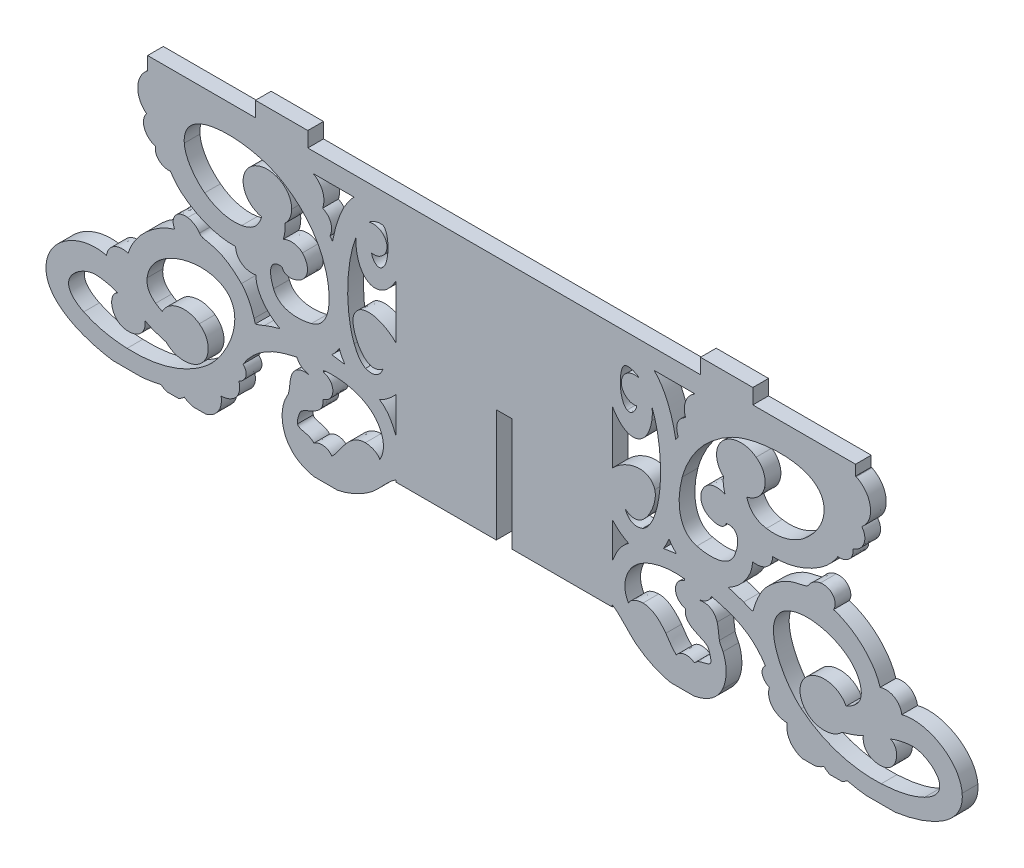
SolidWorks part; units mm, degrees
ref_plane "Plano frontal" through (0, 0, 0) normal (0, 0, 1) x (1, 0, 0)
ref_plane "Plano superior" through (0, 0, 0) normal (0, 1, 0) x (1, 0, 0)
ref_plane "Plano direito" through (0, 0, 0) normal (1, 0, 0) x (0, 0, -1)
sketch "Model" plane through (0, 0, 0) normal (0, 0, 1) x (1, 0, 0)
  line L37 (-5.6284, -71.1175) -> (-5.6464, -70.8746)
  line L38 (-13.1021, -75.7285) -> (-16.0542, -75.7291)
  line L39 (-18.281, -63.636) -> (-19.6289, -63.9795)
  line L40 (-29.8849, -75.7243) -> (-31.4771, -75.7251)
  line L41 (-33.3867, -75.7342) -> (-34.8157, -75.7342)
  line L42 (-37.9546, -75.7342) -> (-41.6837, -75.7314)
  line L43 (-37.2753, -41.5713) -> (-37.2753, -39.8829)
  line L44 (-37.2753, -39.8829) -> (-23.5478, -39.8829)
  line L45 (-23.5478, -39.8829) -> (-23.5478, -37.9569)
  line L46 (-23.5478, -37.9569) -> (-16.8811, -37.9569)
  line L47 (-16.8811, -37.9569) -> (-16.8811, -39.8829)
  line L48 (33.1189, -39.8829) -> (33.1189, -37.9569)
  line L49 (33.1189, -37.9569) -> (39.7856, -37.9569)
  line L50 (39.7856, -37.9569) -> (39.7856, -39.8829)
  line L51 (39.7856, -39.8829) -> (52.8602, -39.8829)
  line L52 (52.8602, -39.8829) -> (52.8602, -41.2009)
  line L53 (52.8602, -41.2009) -> (52.8959, -41.2009)
  line L54 (52.8959, -41.2009) -> (52.9623, -41.2332)
  line L55 (57.9215, -75.7314) -> (54.1924, -75.7342)
  line L56 (51.0535, -75.7342) -> (49.6245, -75.7342)
  line L57 (47.7148, -75.7251) -> (46.1226, -75.7243)
  line L58 (35.8666, -63.9795) -> (34.5187, -63.636)
  line L59 (32.2919, -75.7291) -> (29.3398, -75.7285)
  line L60 (21.8841, -70.8746) -> (21.8661, -71.1175)
  line L61 (21.8661, -71.1175) -> (9.1189, -71.1175)
  line L62 (9.1189, -71.1175) -> (9.1189, -56.74)
  line L63 (9.1189, -56.74) -> (7.1189, -56.74)
  line L64 (7.1189, -56.74) -> (7.1189, -71.1175)
  line L65 (7.1189, -71.1175) -> (-5.6284, -71.1175)
  line L66 (-10.9876, -42.3523) -> (-16.2025, -42.3523)
  line L67 (32.4403, -42.3523) -> (27.2253, -42.3523)
  line L68 (21.8983, -65.9918) -> (21.8983, -61.4665)
  line L69 (21.8983, -55.7779) -> (21.8983, -48.9534)
  line L70 (30.061, -61.1551) -> (28.4015, -61.4015)
  line L71 (-5.6605, -65.9918) -> (-5.6605, -61.4665)
  line L72 (-5.6605, -55.7779) -> (-5.6605, -48.9534)
  line L73 (-13.8232, -61.1551) -> (-12.1638, -61.4015)
  spline S197 degree 3 poles (-5.6464, -70.8746) (-6.5419, -71.3588) (-7.8893, -73.0536) (-8.6517, -73.6479) knots 0.009901 0.009901 0.009901 0.009901 0.019802 0.019802 0.019802 0.019802
  spline S198 degree 3 poles (-8.6517, -73.6479) (-9.9492, -74.6594) (-11.4791, -75.4122) (-13.1021, -75.7285) knots 0.019802 0.019802 0.019802 0.019802 0.029703 0.029703 0.029703 0.029703
  spline S199 degree 3 poles (-16.0542, -75.7291) (-17.6074, -75.4426) (-18.9753, -74.6493) (-19.6727, -73.1749) knots 0.039604 0.039604 0.039604 0.039604 0.049505 0.049505 0.049505 0.049505
  spline S200 degree 3 poles (-19.6727, -73.1749) (-20.2748, -71.9018) (-20.309, -70.2987) (-19.7445, -68.9995) knots 0.049505 0.049505 0.049505 0.049505 0.059406 0.059406 0.059406 0.059406
  spline S201 degree 3 poles (-19.7445, -68.9995) (-19.5924, -68.6493) (-19.3699, -68.3546) (-19.2888, -67.9672) knots 0.059406 0.059406 0.059406 0.059406 0.069307 0.069307 0.069307 0.069307
  spline S202 degree 3 poles (-19.2888, -67.9672) (-19.1614, -67.3578) (-19.1819, -66.7034) (-18.999, -66.1037) knots 0.069307 0.069307 0.069307 0.069307 0.079208 0.079208 0.079208 0.079208
  spline S203 degree 3 poles (-18.999, -66.1037) (-18.6689, -65.0219) (-17.8333, -64.6183) (-16.8102, -64.8106) knots 0.079208 0.079208 0.079208 0.079208 0.089109 0.089109 0.089109 0.089109
  spline S204 degree 3 poles (-16.8102, -64.8106) (-16.8066, -64.7918) (-16.8024, -64.7729) (-16.7979, -64.7539) knots 0.089109 0.089109 0.089109 0.089109 0.09901 0.09901 0.09901 0.09901
  spline S205 degree 3 poles (-16.7979, -64.7539) (-17.4996, -64.6554) (-17.9964, -64.2686) (-18.281, -63.636) knots 0.09901 0.09901 0.09901 0.09901 0.108911 0.108911 0.108911 0.108911
  spline S206 degree 3 poles (-19.6289, -63.9795) (-21.9055, -64.5921) (-23.8126, -65.7446) (-25.137, -67.8442) knots 0.118812 0.118812 0.118812 0.118812 0.128713 0.128713 0.128713 0.128713
  spline S207 degree 3 poles (-25.137, -67.8442) (-24.3471, -68.5533) (-24.768, -69.5566) (-25.6484, -69.984) knots 0.128713 0.128713 0.128713 0.128713 0.138614 0.138614 0.138614 0.138614
  spline S208 degree 3 poles (-25.6484, -69.984) (-25.2197, -71.4939) (-26.2828, -72.6736) (-27.9206, -72.7687) knots 0.138614 0.138614 0.138614 0.138614 0.148515 0.148515 0.148515 0.148515
  spline S209 degree 3 poles (-27.9206, -72.7687) (-27.6704, -74.1792) (-28.5691, -75.382) (-29.8849, -75.7243) knots 0.148515 0.148515 0.148515 0.148515 0.158416 0.158416 0.158416 0.158416
  spline S210 degree 3 poles (-31.4771, -75.7251) (-31.8723, -75.6269) (-32.2526, -75.4578) (-32.6065, -75.2243) knots 0.168317 0.168317 0.168317 0.168317 0.178218 0.178218 0.178218 0.178218
  spline S211 degree 3 poles (-32.6065, -75.2243) (-32.7813, -75.3936) (-33.1597, -75.6888) (-33.3867, -75.7342) knots 0.178218 0.178218 0.178218 0.178218 0.188119 0.188119 0.188119 0.188119
  spline S212 degree 3 poles (-34.8157, -75.7342) (-35.0116, -75.6974) (-35.4128, -75.4422) (-35.5882, -75.3144) knots 0.19802 0.19802 0.19802 0.19802 0.207921 0.207921 0.207921 0.207921
  spline S213 degree 3 poles (-35.5882, -75.3144) (-36.1338, -75.4582) (-37.442, -75.702) (-37.9546, -75.7342) knots 0.207921 0.207921 0.207921 0.207921 0.217822 0.217822 0.217822 0.217822
  spline S214 degree 3 poles (-41.6837, -75.7314) (-44.9016, -75.2916) (-50.559, -73.5038) (-50.1979, -69.3793) knots 0.227723 0.227723 0.227723 0.227723 0.237624 0.237624 0.237624 0.237624
  spline S215 degree 3 poles (-50.1979, -69.3793) (-49.9051, -66.0319) (-45.7279, -63.6924) (-42.5097, -64.5533) knots 0.237624 0.237624 0.237624 0.237624 0.247525 0.247525 0.247525 0.247525
  spline S216 degree 3 poles (-42.5097, -64.5533) (-42.3406, -63.309) (-41.1513, -62.4945) (-39.7553, -62.9251) knots 0.247525 0.247525 0.247525 0.247525 0.257426 0.257426 0.257426 0.257426
  spline S217 degree 3 poles (-39.7553, -62.9251) (-38.9652, -60.3066) (-36.3648, -58.0655) (-33.825, -57.3134) knots 0.257426 0.257426 0.257426 0.257426 0.267327 0.267327 0.267327 0.267327
  spline S218 degree 3 poles (-33.825, -57.3134) (-34.4145, -56.2855) (-33.6513, -54.9988) (-32.1639, -55.1959) knots 0.267327 0.267327 0.267327 0.267327 0.277228 0.277228 0.277228 0.277228
  spline S219 degree 3 poles (-32.1639, -55.1959) (-31.6489, -55.2641) (-30.977, -55.6469) (-30.6727, -56.1655) knots 0.277228 0.277228 0.277228 0.277228 0.287129 0.287129 0.287129 0.287129
  spline S220 degree 3 poles (-30.6727, -56.1655) (-30.2008, -56.97) (-28.3124, -56.0095) (-25.3267, -59.0606) knots 0.287129 0.287129 0.287129 0.287129 0.29703 0.29703 0.29703 0.29703
  spline S221 degree 3 poles (-25.3267, -59.0606) (-24.602, -59.801) (-24.0346, -61.0226) (-23.718, -62.0965) knots 0.29703 0.29703 0.29703 0.29703 0.306931 0.306931 0.306931 0.306931
  spline S222 degree 3 poles (-23.718, -62.0965) (-23.6918, -62.1858) (-23.611, -62.5128) (-23.5594, -62.6316) knots 0.306931 0.306931 0.306931 0.306931 0.316832 0.316832 0.316832 0.316832
  spline S223 degree 3 poles (-23.5594, -62.6316) (-23.2891, -62.5994) (-22.6447, -62.3095) (-22.3768, -62.2085) knots 0.316832 0.316832 0.316832 0.316832 0.326733 0.326733 0.326733 0.326733
  spline S224 degree 3 poles (-22.3768, -62.2085) (-21.7257, -61.9633) (-21.0761, -61.7478) (-20.4179, -61.5711) knots 0.326733 0.326733 0.326733 0.326733 0.336634 0.336634 0.336634 0.336634
  spline S225 degree 3 poles (-20.4179, -61.5711) (-22.012, -60.7087) (-23.4449, -59.0724) (-23.5064, -57.1855) knots 0.336634 0.336634 0.336634 0.336634 0.346535 0.346535 0.346535 0.346535
  spline S226 degree 3 poles (-23.5064, -57.1855) (-24.7892, -57.4359) (-26.0243, -56.7031) (-26.0724, -55.3434) knots 0.346535 0.346535 0.346535 0.346535 0.356436 0.356436 0.356436 0.356436
  spline S227 degree 3 poles (-26.0724, -55.3434) (-28.4957, -55.44) (-31.1466, -54.4236) (-32.9791, -52.8434) knots 0.356436 0.356436 0.356436 0.356436 0.366337 0.366337 0.366337 0.366337
  spline S228 degree 3 poles (-32.9791, -52.8434) (-33.492, -52.401) (-33.9776, -51.8123) (-34.3711, -51.1973) knots 0.366337 0.366337 0.366337 0.366337 0.376238 0.376238 0.376238 0.376238
  spline S229 degree 3 poles (-34.3711, -51.1973) (-35.3634, -51.3239) (-36.4953, -50.5348) (-36.2723, -49.4) knots 0.376238 0.376238 0.376238 0.376238 0.386139 0.386139 0.386139 0.386139
  spline S230 degree 3 poles (-36.2723, -49.4) (-37.635, -48.9585) (-38.2812, -47.4627) (-37.4127, -46.3692) knots 0.386139 0.386139 0.386139 0.386139 0.39604 0.39604 0.39604 0.39604
  spline S231 degree 3 poles (-37.4127, -46.3692) (-39.0338, -45.0675) (-38.818, -42.7399) (-37.2753, -41.5713) knots 0.39604 0.39604 0.39604 0.39604 0.405941 0.405941 0.405941 0.405941
  spline S232 degree 3 poles (-16.8811, -39.8829) (24.2554, -39.8829) (-8.0177, -39.8829) (33.1189, -39.8829) knots 0.455446 0.455446 0.455446 0.455446 0.465347 0.465347 0.465347 0.465347
  spline S233 degree 3 poles (52.9623, -41.2332) (54.9872, -42.2202) (55.4482, -44.9256) (53.6504, -46.3692) knots 0.534653 0.534653 0.534653 0.534653 0.544554 0.544554 0.544554 0.544554
  spline S234 degree 3 poles (53.6504, -46.3692) (54.519, -47.4627) (53.8727, -48.9585) (52.5101, -49.4) knots 0.544554 0.544554 0.544554 0.544554 0.554455 0.554455 0.554455 0.554455
  spline S235 degree 3 poles (52.5101, -49.4) (52.733, -50.5348) (51.6012, -51.3239) (50.6088, -51.1973) knots 0.554455 0.554455 0.554455 0.554455 0.564356 0.564356 0.564356 0.564356
  spline S236 degree 3 poles (50.6088, -51.1973) (50.2153, -51.8123) (49.7298, -52.401) (49.2168, -52.8434) knots 0.564356 0.564356 0.564356 0.564356 0.574257 0.574257 0.574257 0.574257
  spline S237 degree 3 poles (49.2168, -52.8434) (47.3843, -54.4236) (44.7334, -55.44) (42.3101, -55.3434) knots 0.574257 0.574257 0.574257 0.574257 0.584158 0.584158 0.584158 0.584158
  spline S238 degree 3 poles (42.3101, -55.3434) (42.262, -56.7031) (41.027, -57.4359) (39.7442, -57.1855) knots 0.584158 0.584158 0.584158 0.584158 0.594059 0.594059 0.594059 0.594059
  spline S239 degree 3 poles (39.7442, -57.1855) (39.6827, -59.0724) (38.2497, -60.7087) (36.6556, -61.5711) knots 0.594059 0.594059 0.594059 0.594059 0.60396 0.60396 0.60396 0.60396
  spline S240 degree 3 poles (36.6556, -61.5711) (37.3138, -61.7478) (37.9634, -61.9633) (38.6145, -62.2085) knots 0.60396 0.60396 0.60396 0.60396 0.613861 0.613861 0.613861 0.613861
  spline S241 degree 3 poles (38.6145, -62.2085) (38.8825, -62.3095) (39.5268, -62.5994) (39.7971, -62.6316) knots 0.613861 0.613861 0.613861 0.613861 0.623762 0.623762 0.623762 0.623762
  spline S242 degree 3 poles (39.7971, -62.6316) (39.8487, -62.5128) (39.9295, -62.1858) (39.9557, -62.0965) knots 0.623762 0.623762 0.623762 0.623762 0.633663 0.633663 0.633663 0.633663
  spline S243 degree 3 poles (39.9557, -62.0965) (40.2723, -61.0226) (40.8398, -59.801) (41.5644, -59.0606) knots 0.633663 0.633663 0.633663 0.633663 0.643564 0.643564 0.643564 0.643564
  spline S244 degree 3 poles (41.5644, -59.0606) (44.5501, -56.0095) (46.4385, -56.97) (46.9105, -56.1655) knots 0.643564 0.643564 0.643564 0.643564 0.653465 0.653465 0.653465 0.653465
  spline S245 degree 3 poles (46.9105, -56.1655) (47.2147, -55.6469) (47.8867, -55.2641) (48.4016, -55.1959) knots 0.653465 0.653465 0.653465 0.653465 0.663366 0.663366 0.663366 0.663366
  spline S246 degree 3 poles (48.4016, -55.1959) (49.8891, -54.9988) (50.6522, -56.2855) (50.0628, -57.3134) knots 0.663366 0.663366 0.663366 0.663366 0.673267 0.673267 0.673267 0.673267
  spline S247 degree 3 poles (50.0628, -57.3134) (52.6026, -58.0655) (55.2029, -60.3066) (55.9931, -62.9251) knots 0.673267 0.673267 0.673267 0.673267 0.683168 0.683168 0.683168 0.683168
  spline S248 degree 3 poles (55.9931, -62.9251) (57.389, -62.4945) (58.5783, -63.309) (58.7475, -64.5533) knots 0.683168 0.683168 0.683168 0.683168 0.693069 0.693069 0.693069 0.693069
  spline S249 degree 3 poles (58.7475, -64.5533) (61.9656, -63.6924) (66.1428, -66.0319) (66.4357, -69.3793) knots 0.693069 0.693069 0.693069 0.693069 0.70297 0.70297 0.70297 0.70297
  spline S250 degree 3 poles (66.4357, -69.3793) (66.7967, -73.5038) (61.1393, -75.2916) (57.9215, -75.7314) knots 0.70297 0.70297 0.70297 0.70297 0.712871 0.712871 0.712871 0.712871
  spline S251 degree 3 poles (54.1924, -75.7342) (53.6797, -75.702) (52.3716, -75.4582) (51.826, -75.3144) knots 0.722772 0.722772 0.722772 0.722772 0.732673 0.732673 0.732673 0.732673
  spline S252 degree 3 poles (51.826, -75.3144) (51.6505, -75.4422) (51.2493, -75.6974) (51.0535, -75.7342) knots 0.732673 0.732673 0.732673 0.732673 0.742574 0.742574 0.742574 0.742574
  spline S253 degree 3 poles (49.6245, -75.7342) (49.3974, -75.6888) (49.019, -75.3936) (48.8442, -75.2243) knots 0.752475 0.752475 0.752475 0.752475 0.762376 0.762376 0.762376 0.762376
  spline S254 degree 3 poles (48.8442, -75.2243) (48.4903, -75.4578) (48.11, -75.6269) (47.7148, -75.7251) knots 0.762376 0.762376 0.762376 0.762376 0.772277 0.772277 0.772277 0.772277
  spline S255 degree 3 poles (46.1226, -75.7243) (44.8069, -75.382) (43.9081, -74.1792) (44.1584, -72.7687) knots 0.782178 0.782178 0.782178 0.782178 0.792079 0.792079 0.792079 0.792079
  spline S256 degree 3 poles (44.1584, -72.7687) (42.5205, -72.6736) (41.4574, -71.4939) (41.8862, -69.984) knots 0.792079 0.792079 0.792079 0.792079 0.80198 0.80198 0.80198 0.80198
  spline S257 degree 3 poles (41.8862, -69.984) (41.0057, -69.5566) (40.5849, -68.5533) (41.3748, -67.8442) knots 0.80198 0.80198 0.80198 0.80198 0.811881 0.811881 0.811881 0.811881
  spline S258 degree 3 poles (41.3748, -67.8442) (40.0503, -65.7446) (38.1433, -64.5921) (35.8666, -63.9795) knots 0.811881 0.811881 0.811881 0.811881 0.821782 0.821782 0.821782 0.821782
  spline S259 degree 3 poles (34.5187, -63.636) (34.2342, -64.2686) (33.7373, -64.6554) (33.0357, -64.7539) knots 0.831683 0.831683 0.831683 0.831683 0.841584 0.841584 0.841584 0.841584
  spline S260 degree 3 poles (33.0357, -64.7539) (33.0401, -64.7729) (33.0443, -64.7918) (33.048, -64.8106) knots 0.841584 0.841584 0.841584 0.841584 0.851485 0.851485 0.851485 0.851485
  spline S261 degree 3 poles (33.048, -64.8106) (34.071, -64.6183) (34.9066, -65.0219) (35.2367, -66.1037) knots 0.851485 0.851485 0.851485 0.851485 0.861386 0.861386 0.861386 0.861386
  spline S262 degree 3 poles (35.2367, -66.1037) (35.4196, -66.7034) (35.3992, -67.3578) (35.5266, -67.9672) knots 0.861386 0.861386 0.861386 0.861386 0.871287 0.871287 0.871287 0.871287
  spline S263 degree 3 poles (35.5266, -67.9672) (35.6076, -68.3546) (35.8302, -68.6493) (35.9823, -68.9995) knots 0.871287 0.871287 0.871287 0.871287 0.881188 0.881188 0.881188 0.881188
  spline S264 degree 3 poles (35.9823, -68.9995) (36.5467, -70.2987) (36.5126, -71.9018) (35.9104, -73.1749) knots 0.881188 0.881188 0.881188 0.881188 0.891089 0.891089 0.891089 0.891089
  spline S265 degree 3 poles (35.9104, -73.1749) (35.2131, -74.6493) (33.8452, -75.4426) (32.2919, -75.7291) knots 0.891089 0.891089 0.891089 0.891089 0.90099 0.90099 0.90099 0.90099
  spline S266 degree 3 poles (29.3398, -75.7285) (27.7168, -75.4122) (26.1869, -74.6594) (24.8894, -73.6479) knots 0.910891 0.910891 0.910891 0.910891 0.920792 0.920792 0.920792 0.920792
  spline S267 degree 3 poles (24.8894, -73.6479) (24.127, -73.0536) (22.7796, -71.3588) (21.8841, -70.8746) knots 0.920792 0.920792 0.920792 0.920792 0.930693 0.930693 0.930693 0.930693
  spline S268 degree 3 poles (-16.2025, -42.3523) (-15.1507, -42.9311) (-14.5218, -44.1493) (-14.9827, -45.5708) knots 0 0 0 0 0.166667 0.166667 0.166667 0.166667
  spline S269 degree 3 poles (-14.9827, -45.5708) (-13.9248, -46.0819) (-13.6065, -47.078) (-14.0462, -48.1542) knots 0.166667 0.166667 0.166667 0.166667 0.333333 0.333333 0.333333 0.333333
  spline S270 degree 3 poles (-14.0462, -48.1542) (-13.9394, -48.3036) (-13.8344, -48.4621) (-13.7323, -48.6243) knots 0.333333 0.333333 0.333333 0.333333 0.5 0.5 0.5 0.5
  spline S271 degree 3 poles (-13.7323, -48.6243) (-13.3251, -46.2966) (-12.4877, -43.8395) (-10.9876, -42.3523) knots 0.5 0.5 0.5 0.5 0.666667 0.666667 0.666667 0.666667
  spline S272 degree 3 poles (27.2253, -42.3523) (28.7254, -43.8395) (29.5629, -46.2966) (29.97, -48.6243) knots 0 0 0 0 0.166667 0.166667 0.166667 0.166667
  spline S273 degree 3 poles (29.97, -48.6243) (30.0721, -48.4621) (30.1772, -48.3036) (30.2839, -48.1542) knots 0.166667 0.166667 0.166667 0.166667 0.333333 0.333333 0.333333 0.333333
  spline S274 degree 3 poles (30.2839, -48.1542) (29.8442, -47.078) (30.1626, -46.0819) (31.2204, -45.5708) knots 0.333333 0.333333 0.333333 0.333333 0.5 0.5 0.5 0.5
  spline S275 degree 3 poles (31.2204, -45.5708) (30.7596, -44.1493) (31.3885, -42.9311) (32.4403, -42.3523) knots 0.5 0.5 0.5 0.5 0.666667 0.666667 0.666667 0.666667
  spline S276 degree 3 poles (21.8983, -61.4665) (22.4767, -62.1138) (23.2107, -62.7157) (23.9781, -63.0524) knots 0.25 0.25 0.25 0.25 0.5 0.5 0.5 0.5
  spline S277 degree 3 poles (23.9781, -63.0524) (22.8318, -63.8652) (22.4114, -64.7538) (21.8983, -65.9918) knots 0.5 0.5 0.5 0.5 1 1 1 1
  spline S278 degree 3 poles (23.5508, -59.4726) (23.9717, -59.8538) (24.5568, -60.0203) (25.0819, -59.8898) knots 0 0 0 0 0.090909 0.090909 0.090909 0.090909
  spline S279 degree 3 poles (25.0819, -59.8898) (26.5124, -59.5344) (27.6791, -56.6553) (27.2955, -55.4657) knots 0.090909 0.090909 0.090909 0.090909 0.181818 0.181818 0.181818 0.181818
  spline S280 degree 3 poles (27.2955, -55.4657) (26.5745, -53.2297) (23.4797, -54.1031) (21.8983, -55.7779) knots 0.181818 0.181818 0.181818 0.181818 0.272727 0.272727 0.272727 0.272727
  spline S281 degree 3 poles (21.8983, -48.9534) (23.715, -52.2071) (26.3849, -51.5086) (26.9173, -48.0577) knots 0.363636 0.363636 0.363636 0.363636 0.454545 0.454545 0.454545 0.454545
  spline S282 degree 3 poles (26.9173, -48.0577) (26.9939, -47.5614) (27.0085, -47.0558) (26.9564, -46.579) knots 0.454545 0.454545 0.454545 0.454545 0.545455 0.545455 0.545455 0.545455
  spline S283 degree 3 poles (26.9564, -46.579) (28.2487, -49.8227) (28.451, -55.2831) (27.213, -58.5173) knots 0.545455 0.545455 0.545455 0.545455 0.636364 0.636364 0.636364 0.636364
  spline S284 degree 3 poles (27.213, -58.5173) (26.9098, -59.3094) (26.4428, -60.1467) (25.7631, -60.5059) knots 0.636364 0.636364 0.636364 0.636364 0.727273 0.727273 0.727273 0.727273
  spline S285 degree 3 poles (25.7631, -60.5059) (25.054, -60.7711) (24.3, -60.7374) (23.8014, -59.9858) knots 0.727273 0.727273 0.727273 0.727273 0.818182 0.818182 0.818182 0.818182
  spline S286 degree 3 poles (23.8014, -59.9858) (23.6985, -59.8307) (23.6152, -59.6568) (23.5508, -59.4726) knots 0.818182 0.818182 0.818182 0.818182 1 1 1 1
  spline S287 degree 3 poles (25.3652, -44.1753) (23.4778, -43.615) (22.2258, -45.7973) (23.6524, -47.0363) knots 0 0 0 0 0.166667 0.166667 0.166667 0.166667
  spline S288 degree 3 poles (23.6524, -47.0363) (24.0428, -47.3753) (24.532, -47.4964) (25.0001, -47.3837) knots 0.166667 0.166667 0.166667 0.166667 0.333333 0.333333 0.333333 0.333333
  spline S289 degree 3 poles (25.0001, -47.3837) (24.9505, -47.8912) (24.3805, -48.7674) (23.7771, -48.4443) knots 0.333333 0.333333 0.333333 0.333333 0.5 0.5 0.5 0.5
  spline S290 degree 3 poles (23.7771, -48.4443) (22.6078, -47.8182) (22.6642, -43.7262) (23.6446, -43.6067) knots 0.5 0.5 0.5 0.5 0.666667 0.666667 0.666667 0.666667
  spline S291 degree 3 poles (23.6446, -43.6067) (24.2518, -43.5328) (24.8926, -43.7954) (25.3652, -44.1753) knots 0.666667 0.666667 0.666667 0.666667 1 1 1 1
  spline S292 degree 3 poles (28.4015, -61.4015) (28.6801, -60.9661) (28.9165, -60.4833) (29.1159, -59.9892) knots 0.25 0.25 0.25 0.25 0.5 0.5 0.5 0.5
  spline S293 degree 3 poles (29.1159, -59.9892) (29.3835, -60.4337) (29.6983, -60.8262) (30.061, -61.1551) knots 0.5 0.5 0.5 0.5 1 1 1 1
  spline S294 degree 3 poles (36.0381, -49.6439) (35.9571, -50.2985) (36.0478, -50.8902) (36.2461, -51.5103) knots 0 0 0 0 0.058824 0.058824 0.058824 0.058824
  spline S295 degree 3 poles (36.2461, -51.5103) (35.4573, -51.1422) (34.4529, -51.158) (33.8083, -51.8027) knots 0.058824 0.058824 0.058824 0.058824 0.117647 0.117647 0.117647 0.117647
  spline S296 degree 3 poles (33.8083, -51.8027) (32.824, -52.7873) (32.906, -54.4153) (34.3932, -55.0923) knots 0.117647 0.117647 0.117647 0.117647 0.176471 0.176471 0.176471 0.176471
  spline S297 degree 3 poles (34.3932, -55.0923) (35.0481, -55.3904) (36.1044, -55.5153) (36.38, -54.6548) knots 0.176471 0.176471 0.176471 0.176471 0.235294 0.235294 0.235294 0.235294
  spline S298 degree 3 poles (36.38, -54.6548) (36.7529, -54.5614) (37.1846, -54.5967) (37.4917, -54.8849) knots 0.235294 0.235294 0.235294 0.235294 0.294118 0.294118 0.294118 0.294118
  spline S299 degree 3 poles (37.4917, -54.8849) (38.1562, -55.5082) (37.7715, -56.8569) (37.4787, -57.5909) knots 0.294118 0.294118 0.294118 0.294118 0.352941 0.352941 0.352941 0.352941
  spline S300 degree 3 poles (37.4787, -57.5909) (36.7026, -59.5363) (34.098, -59.3942) (32.653, -59.0123) knots 0.352941 0.352941 0.352941 0.352941 0.411765 0.411765 0.411765 0.411765
  spline S301 degree 3 poles (32.653, -59.0123) (29.9072, -58.2868) (30.2036, -54.4466) (30.8, -52.3237) knots 0.411765 0.411765 0.411765 0.411765 0.470588 0.470588 0.470588 0.470588
  spline S302 degree 3 poles (30.8, -52.3237) (31.8304, -48.6565) (34.2859, -46.2351) (37.1386, -44.7681) knots 0.470588 0.470588 0.470588 0.470588 0.529412 0.529412 0.529412 0.529412
  spline S303 degree 3 poles (37.1386, -44.7681) (40.7014, -42.9359) (49.1984, -42.4396) (48.8428, -47.2099) knots 0.529412 0.529412 0.529412 0.529412 0.588235 0.588235 0.588235 0.588235
  spline S304 degree 3 poles (48.8428, -47.2099) (48.7201, -48.8558) (47.4807, -50.4334) (46.2401, -51.3905) knots 0.588235 0.588235 0.588235 0.588235 0.647059 0.647059 0.647059 0.647059
  spline S305 degree 3 poles (46.2401, -51.3905) (44.8579, -52.4568) (43.1427, -52.9059) (41.5242, -52.6311) knots 0.647059 0.647059 0.647059 0.647059 0.705882 0.705882 0.705882 0.705882
  spline S306 degree 3 poles (41.5242, -52.6311) (40.1542, -52.3985) (39.3691, -51.6872) (39.004, -50.424) knots 0.705882 0.705882 0.705882 0.705882 0.764706 0.764706 0.764706 0.764706
  spline S307 degree 3 poles (39.004, -50.424) (41.467, -49.8517) (42.2002, -46.9164) (40.2066, -45.4338) knots 0.764706 0.764706 0.764706 0.764706 0.823529 0.823529 0.823529 0.823529
  spline S308 degree 3 poles (40.2066, -45.4338) (38.2649, -43.9897) (35.1699, -45.1675) (35.1699, -47.6557) knots 0.823529 0.823529 0.823529 0.823529 0.882353 0.882353 0.882353 0.882353
  spline S309 degree 3 poles (35.1699, -47.6557) (35.1699, -48.47) (35.5296, -49.1593) (36.0381, -49.6439) knots 0.882353 0.882353 0.882353 0.882353 1 1 1 1
  spline S310 degree 3 poles (51.1493, -70.302) (52.1053, -70.0032) (53.0002, -69.7957) (53.8539, -69.2753) knots 0 0 0 0 0.066667 0.066667 0.066667 0.066667
  spline S311 degree 3 poles (53.8539, -69.2753) (53.6479, -70.8072) (54.9122, -71.6846) (56.3066, -71.4968) knots 0.066667 0.066667 0.066667 0.066667 0.133333 0.133333 0.133333 0.133333
  spline S312 degree 3 poles (56.3066, -71.4968) (58.3124, -71.2268) (58.6016, -68.4463) (57.3006, -67.9677) knots 0.133333 0.133333 0.133333 0.133333 0.2 0.2 0.2 0.2
  spline S313 degree 3 poles (57.3006, -67.9677) (58.0363, -67.628) (59.5416, -67.2987) (60.365, -67.3633) knots 0.2 0.2 0.2 0.2 0.266667 0.266667 0.266667 0.266667
  spline S314 degree 3 poles (60.365, -67.3633) (62.3074, -67.5155) (65.7576, -70.1563) (61.6432, -72.2178) knots 0.266667 0.266667 0.266667 0.266667 0.333333 0.333333 0.333333 0.333333
  spline S315 degree 3 poles (61.6432, -72.2178) (59.9784, -73.0519) (57.9677, -73.3982) (56.1294, -73.4798) knots 0.333333 0.333333 0.333333 0.333333 0.4 0.4 0.4 0.4
  spline S316 degree 3 poles (56.1294, -73.4798) (52.5719, -73.6375) (48.9495, -72.7449) (45.962, -70.2917) knots 0.4 0.4 0.4 0.4 0.466667 0.466667 0.466667 0.466667
  spline S317 degree 3 poles (45.962, -70.2917) (43.1531, -67.9854) (39.8805, -61.0969) (45.4357, -59.9631) knots 0.466667 0.466667 0.466667 0.466667 0.533333 0.533333 0.533333 0.533333
  spline S318 degree 3 poles (45.4357, -59.9631) (48.3962, -59.3589) (53.1811, -61.0898) (53.572, -64.4293) knots 0.533333 0.533333 0.533333 0.533333 0.6 0.6 0.6 0.6
  spline S319 degree 3 poles (53.572, -64.4293) (53.6908, -65.4442) (53.2531, -66.1246) (52.4812, -66.6814) knots 0.6 0.6 0.6 0.6 0.666667 0.666667 0.666667 0.666667
  spline S320 degree 3 poles (52.4812, -66.6814) (52.2802, -66.8263) (51.9406, -67.0451) (51.655, -67.1704) knots 0.666667 0.666667 0.666667 0.666667 0.733333 0.733333 0.733333 0.733333
  spline S321 degree 3 poles (51.655, -67.1704) (50.7762, -65.4229) (48.3934, -65.0916) (46.935, -66.1762) knots 0.733333 0.733333 0.733333 0.733333 0.8 0.8 0.8 0.8
  spline S322 degree 3 poles (46.935, -66.1762) (44.6881, -67.8471) (45.9755, -71.2273) (48.8706, -71.2273) knots 0.8 0.8 0.8 0.8 0.866667 0.866667 0.866667 0.866667
  spline S323 degree 3 poles (48.8706, -71.2273) (49.6737, -71.2273) (50.5239, -70.9372) (51.1493, -70.302) knots 0.866667 0.866667 0.866667 0.866667 1 1 1 1
  spline S324 degree 3 poles (23.9524, -69.659) (23.2017, -68.3663) (23.4088, -66.9809) (24.2064, -65.7629) knots 0 0 0 0 0.083333 0.083333 0.083333 0.083333
  spline S325 degree 3 poles (24.2064, -65.7629) (25.5334, -63.7363) (28.7512, -63.084) (31.1004, -63.4128) knots 0.083333 0.083333 0.083333 0.083333 0.166667 0.166667 0.166667 0.166667
  spline S326 degree 3 poles (31.1004, -63.4128) (31.0988, -63.4819) (31.1027, -63.5511) (31.1118, -63.6196) knots 0.166667 0.166667 0.166667 0.166667 0.25 0.25 0.25 0.25
  spline S327 degree 3 poles (31.1118, -63.6196) (29.5784, -63.9869) (29.4562, -66.1418) (31.2042, -66.6447) knots 0.25 0.25 0.25 0.25 0.333333 0.333333 0.333333 0.333333
  spline S328 degree 3 poles (31.2042, -66.6447) (30.9074, -68.6379) (33.7456, -68.7201) (34.1184, -69.5314) knots 0.333333 0.333333 0.333333 0.333333 0.416667 0.416667 0.416667 0.416667
  spline S329 degree 3 poles (34.1184, -69.5314) (34.2574, -69.8338) (34.5133, -70.6115) (34.4225, -70.9571) knots 0.416667 0.416667 0.416667 0.416667 0.5 0.5 0.5 0.5
  spline S330 degree 3 poles (34.4225, -70.9571) (34.2683, -71.5431) (32.9564, -71.2707) (32.3438, -72.0431) knots 0.5 0.5 0.5 0.5 0.583333 0.583333 0.583333 0.583333
  spline S331 degree 3 poles (32.3438, -72.0431) (31.642, -71.514) (30.5964, -71.5817) (30.045, -72.3235) knots 0.583333 0.583333 0.583333 0.583333 0.666667 0.666667 0.666667 0.666667
  spline S332 degree 3 poles (30.045, -72.3235) (29.416, -71.7429) (29.1977, -71.2589) (28.7045, -70.6024) knots 0.666667 0.666667 0.666667 0.666667 0.75 0.75 0.75 0.75
  spline S333 degree 3 poles (28.7045, -70.6024) (28.0003, -69.665) (27.0428, -68.694) (25.7952, -68.7199) knots 0.75 0.75 0.75 0.75 0.833333 0.833333 0.833333 0.833333
  spline S334 degree 3 poles (25.7952, -68.7199) (25.1347, -68.7335) (24.2483, -69.0072) (23.9524, -69.659) knots 0.833333 0.833333 0.833333 0.833333 1 1 1 1
  spline S335 degree 3 poles (-5.6605, -61.4665) (-6.239, -62.1138) (-6.9729, -62.7157) (-7.7404, -63.0524) knots 0.25 0.25 0.25 0.25 0.5 0.5 0.5 0.5
  spline S336 degree 3 poles (-7.7404, -63.0524) (-6.5941, -63.8652) (-6.1737, -64.7538) (-5.6605, -65.9918) knots 0.5 0.5 0.5 0.5 1 1 1 1
  spline S337 degree 3 poles (-7.3131, -59.4726) (-7.734, -59.8538) (-8.3191, -60.0203) (-8.8441, -59.8898) knots 0 0 0 0 0.090909 0.090909 0.090909 0.090909
  spline S338 degree 3 poles (-8.8441, -59.8898) (-10.2747, -59.5344) (-11.4413, -56.6553) (-11.0577, -55.4657) knots 0.090909 0.090909 0.090909 0.090909 0.181818 0.181818 0.181818 0.181818
  spline S339 degree 3 poles (-11.0577, -55.4657) (-10.3368, -53.2297) (-7.2419, -54.1031) (-5.6605, -55.7779) knots 0.181818 0.181818 0.181818 0.181818 0.272727 0.272727 0.272727 0.272727
  spline S340 degree 3 poles (-5.6605, -48.9534) (-7.4773, -52.2071) (-10.1472, -51.5086) (-10.6795, -48.0577) knots 0.363636 0.363636 0.363636 0.363636 0.454545 0.454545 0.454545 0.454545
  spline S341 degree 3 poles (-10.6795, -48.0577) (-10.7561, -47.5614) (-10.7708, -47.0558) (-10.7187, -46.579) knots 0.454545 0.454545 0.454545 0.454545 0.545455 0.545455 0.545455 0.545455
  spline S342 degree 3 poles (-10.7187, -46.579) (-12.011, -49.8227) (-12.2132, -55.2831) (-10.9753, -58.5173) knots 0.545455 0.545455 0.545455 0.545455 0.636364 0.636364 0.636364 0.636364
  spline S343 degree 3 poles (-10.9753, -58.5173) (-10.6721, -59.3094) (-10.205, -60.1467) (-9.5254, -60.5059) knots 0.636364 0.636364 0.636364 0.636364 0.727273 0.727273 0.727273 0.727273
  spline S344 degree 3 poles (-9.5254, -60.5059) (-8.8163, -60.7711) (-8.0623, -60.7374) (-7.5637, -59.9858) knots 0.727273 0.727273 0.727273 0.727273 0.818182 0.818182 0.818182 0.818182
  spline S345 degree 3 poles (-7.5637, -59.9858) (-7.4608, -59.8307) (-7.3775, -59.6568) (-7.3131, -59.4726) knots 0.818182 0.818182 0.818182 0.818182 1 1 1 1
  spline S346 degree 3 poles (-9.1275, -44.1753) (-7.2401, -43.615) (-5.9881, -45.7973) (-7.4147, -47.0363) knots 0 0 0 0 0.166667 0.166667 0.166667 0.166667
  spline S347 degree 3 poles (-7.4147, -47.0363) (-7.805, -47.3753) (-8.2942, -47.4964) (-8.7624, -47.3837) knots 0.166667 0.166667 0.166667 0.166667 0.333333 0.333333 0.333333 0.333333
  spline S348 degree 3 poles (-8.7624, -47.3837) (-8.7128, -47.8912) (-8.1428, -48.7674) (-7.5394, -48.4443) knots 0.333333 0.333333 0.333333 0.333333 0.5 0.5 0.5 0.5
  spline S349 degree 3 poles (-7.5394, -48.4443) (-6.3701, -47.8182) (-6.4265, -43.7262) (-7.4069, -43.6067) knots 0.5 0.5 0.5 0.5 0.666667 0.666667 0.666667 0.666667
  spline S350 degree 3 poles (-7.4069, -43.6067) (-8.014, -43.5328) (-8.6549, -43.7954) (-9.1275, -44.1753) knots 0.666667 0.666667 0.666667 0.666667 1 1 1 1
  spline S351 degree 3 poles (-12.1638, -61.4015) (-12.4424, -60.9661) (-12.6788, -60.4833) (-12.8781, -59.9892) knots 0.25 0.25 0.25 0.25 0.5 0.5 0.5 0.5
  spline S352 degree 3 poles (-12.8781, -59.9892) (-13.1457, -60.4337) (-13.4606, -60.8262) (-13.8232, -61.1551) knots 0.5 0.5 0.5 0.5 1 1 1 1
  spline S353 degree 3 poles (-19.8004, -49.6439) (-19.7193, -50.2985) (-19.81, -50.8902) (-20.0084, -51.5103) knots 0 0 0 0 0.058824 0.058824 0.058824 0.058824
  spline S354 degree 3 poles (-20.0084, -51.5103) (-19.2196, -51.1422) (-18.2152, -51.158) (-17.5705, -51.8027) knots 0.058824 0.058824 0.058824 0.058824 0.117647 0.117647 0.117647 0.117647
  spline S355 degree 3 poles (-17.5705, -51.8027) (-16.5862, -52.7873) (-16.6682, -54.4153) (-18.1554, -55.0923) knots 0.117647 0.117647 0.117647 0.117647 0.176471 0.176471 0.176471 0.176471
  spline S356 degree 3 poles (-18.1554, -55.0923) (-18.8104, -55.3904) (-19.8667, -55.5153) (-20.1422, -54.6548) knots 0.176471 0.176471 0.176471 0.176471 0.235294 0.235294 0.235294 0.235294
  spline S357 degree 3 poles (-20.1422, -54.6548) (-20.5152, -54.5614) (-20.9468, -54.5967) (-21.254, -54.8849) knots 0.235294 0.235294 0.235294 0.235294 0.294118 0.294118 0.294118 0.294118
  spline S358 degree 3 poles (-21.254, -54.8849) (-21.9184, -55.5082) (-21.5338, -56.8569) (-21.2409, -57.5909) knots 0.294118 0.294118 0.294118 0.294118 0.352941 0.352941 0.352941 0.352941
  spline S359 degree 3 poles (-21.2409, -57.5909) (-20.4648, -59.5363) (-17.8602, -59.3942) (-16.4152, -59.0123) knots 0.352941 0.352941 0.352941 0.352941 0.411765 0.411765 0.411765 0.411765
  spline S360 degree 3 poles (-16.4152, -59.0123) (-13.6695, -58.2868) (-13.9659, -54.4466) (-14.5623, -52.3237) knots 0.411765 0.411765 0.411765 0.411765 0.470588 0.470588 0.470588 0.470588
  spline S361 degree 3 poles (-14.5623, -52.3237) (-15.5927, -48.6565) (-18.0482, -46.2351) (-20.9008, -44.7681) knots 0.470588 0.470588 0.470588 0.470588 0.529412 0.529412 0.529412 0.529412
  spline S362 degree 3 poles (-20.9008, -44.7681) (-24.4637, -42.9359) (-32.9607, -42.4396) (-32.6051, -47.2099) knots 0.529412 0.529412 0.529412 0.529412 0.588235 0.588235 0.588235 0.588235
  spline S363 degree 3 poles (-32.6051, -47.2099) (-32.4823, -48.8558) (-31.2429, -50.4334) (-30.0023, -51.3905) knots 0.588235 0.588235 0.588235 0.588235 0.647059 0.647059 0.647059 0.647059
  spline S364 degree 3 poles (-30.0023, -51.3905) (-28.6202, -52.4568) (-26.905, -52.9059) (-25.2865, -52.6311) knots 0.647059 0.647059 0.647059 0.647059 0.705882 0.705882 0.705882 0.705882
  spline S365 degree 3 poles (-25.2865, -52.6311) (-23.9165, -52.3985) (-23.1313, -51.6872) (-22.7663, -50.424) knots 0.705882 0.705882 0.705882 0.705882 0.764706 0.764706 0.764706 0.764706
  spline S366 degree 3 poles (-22.7663, -50.424) (-25.2292, -49.8517) (-25.9624, -46.9164) (-23.9688, -45.4338) knots 0.764706 0.764706 0.764706 0.764706 0.823529 0.823529 0.823529 0.823529
  spline S367 degree 3 poles (-23.9688, -45.4338) (-22.0271, -43.9897) (-18.9321, -45.1675) (-18.9321, -47.6557) knots 0.823529 0.823529 0.823529 0.823529 0.882353 0.882353 0.882353 0.882353
  spline S368 degree 3 poles (-18.9321, -47.6557) (-18.9321, -48.47) (-19.2919, -49.1593) (-19.8004, -49.6439) knots 0.882353 0.882353 0.882353 0.882353 1 1 1 1
  spline S369 degree 3 poles (-34.9116, -70.302) (-35.8675, -70.0032) (-36.7624, -69.7957) (-37.6162, -69.2753) knots 0 0 0 0 0.066667 0.066667 0.066667 0.066667
  spline S370 degree 3 poles (-37.6162, -69.2753) (-37.4102, -70.8072) (-38.6744, -71.6846) (-40.0688, -71.4968) knots 0.066667 0.066667 0.066667 0.066667 0.133333 0.133333 0.133333 0.133333
  spline S371 degree 3 poles (-40.0688, -71.4968) (-42.0746, -71.2268) (-42.3638, -68.4463) (-41.0629, -67.9677) knots 0.133333 0.133333 0.133333 0.133333 0.2 0.2 0.2 0.2
  spline S372 degree 3 poles (-41.0629, -67.9677) (-41.7985, -67.628) (-43.3038, -67.2987) (-44.1273, -67.3633) knots 0.2 0.2 0.2 0.2 0.266667 0.266667 0.266667 0.266667
  spline S373 degree 3 poles (-44.1273, -67.3633) (-46.0697, -67.5155) (-49.5199, -70.1563) (-45.4055, -72.2178) knots 0.266667 0.266667 0.266667 0.266667 0.333333 0.333333 0.333333 0.333333
  spline S374 degree 3 poles (-45.4055, -72.2178) (-43.7407, -73.0519) (-41.7299, -73.3982) (-39.8917, -73.4798) knots 0.333333 0.333333 0.333333 0.333333 0.4 0.4 0.4 0.4
  spline S375 degree 3 poles (-39.8917, -73.4798) (-36.3342, -73.6375) (-32.7117, -72.7449) (-29.7243, -70.2917) knots 0.4 0.4 0.4 0.4 0.466667 0.466667 0.466667 0.466667
  spline S376 degree 3 poles (-29.7243, -70.2917) (-26.9154, -67.9854) (-23.6427, -61.0969) (-29.198, -59.9631) knots 0.466667 0.466667 0.466667 0.466667 0.533333 0.533333 0.533333 0.533333
  spline S377 degree 3 poles (-29.198, -59.9631) (-32.1585, -59.3589) (-36.9434, -61.0898) (-37.3343, -64.4293) knots 0.533333 0.533333 0.533333 0.533333 0.6 0.6 0.6 0.6
  spline S378 degree 3 poles (-37.3343, -64.4293) (-37.4531, -65.4442) (-37.0154, -66.1246) (-36.2434, -66.6814) knots 0.6 0.6 0.6 0.6 0.666667 0.666667 0.666667 0.666667
  spline S379 degree 3 poles (-36.2434, -66.6814) (-36.0425, -66.8263) (-35.7029, -67.0451) (-35.4172, -67.1704) knots 0.666667 0.666667 0.666667 0.666667 0.733333 0.733333 0.733333 0.733333
  spline S380 degree 3 poles (-35.4172, -67.1704) (-34.5385, -65.4229) (-32.1557, -65.0916) (-30.6972, -66.1762) knots 0.733333 0.733333 0.733333 0.733333 0.8 0.8 0.8 0.8
  spline S381 degree 3 poles (-30.6972, -66.1762) (-28.4504, -67.8471) (-29.7377, -71.2273) (-32.6329, -71.2273) knots 0.8 0.8 0.8 0.8 0.866667 0.866667 0.866667 0.866667
  spline S382 degree 3 poles (-32.6329, -71.2273) (-33.4359, -71.2273) (-34.2861, -70.9372) (-34.9116, -70.302) knots 0.866667 0.866667 0.866667 0.866667 1 1 1 1
  spline S383 degree 3 poles (-7.7147, -69.659) (-6.9639, -68.3663) (-7.1711, -66.9809) (-7.9686, -65.7629) knots 0 0 0 0 0.083333 0.083333 0.083333 0.083333
  spline S384 degree 3 poles (-7.9686, -65.7629) (-9.2957, -63.7363) (-12.5134, -63.084) (-14.8627, -63.4128) knots 0.083333 0.083333 0.083333 0.083333 0.166667 0.166667 0.166667 0.166667
  spline S385 degree 3 poles (-14.8627, -63.4128) (-14.8611, -63.4819) (-14.865, -63.5511) (-14.8741, -63.6196) knots 0.166667 0.166667 0.166667 0.166667 0.25 0.25 0.25 0.25
  spline S386 degree 3 poles (-14.8741, -63.6196) (-13.3407, -63.9869) (-13.2185, -66.1418) (-14.9665, -66.6447) knots 0.25 0.25 0.25 0.25 0.333333 0.333333 0.333333 0.333333
  spline S387 degree 3 poles (-14.9665, -66.6447) (-14.6696, -68.6379) (-17.5079, -68.7201) (-17.8806, -69.5314) knots 0.333333 0.333333 0.333333 0.333333 0.416667 0.416667 0.416667 0.416667
  spline S388 degree 3 poles (-17.8806, -69.5314) (-18.0197, -69.8338) (-18.2756, -70.6115) (-18.1847, -70.9571) knots 0.416667 0.416667 0.416667 0.416667 0.5 0.5 0.5 0.5
  spline S389 degree 3 poles (-18.1847, -70.9571) (-18.0306, -71.5431) (-16.7186, -71.2707) (-16.106, -72.0431) knots 0.5 0.5 0.5 0.5 0.583333 0.583333 0.583333 0.583333
  spline S390 degree 3 poles (-16.106, -72.0431) (-15.4043, -71.514) (-14.3587, -71.5817) (-13.8072, -72.3235) knots 0.583333 0.583333 0.583333 0.583333 0.666667 0.666667 0.666667 0.666667
  spline S391 degree 3 poles (-13.8072, -72.3235) (-13.1783, -71.7429) (-12.9599, -71.2589) (-12.4668, -70.6024) knots 0.666667 0.666667 0.666667 0.666667 0.75 0.75 0.75 0.75
  spline S392 degree 3 poles (-12.4668, -70.6024) (-11.7626, -69.665) (-10.8051, -68.694) (-9.5574, -68.7199) knots 0.75 0.75 0.75 0.75 0.833333 0.833333 0.833333 0.833333
  spline S393 degree 3 poles (-9.5574, -68.7199) (-8.897, -68.7335) (-8.0106, -69.0072) (-7.7147, -69.659) knots 0.833333 0.833333 0.833333 0.833333 1 1 1 1
extrude "Ressalto-extrusão1" add sketch "Model" along normal blind 2
